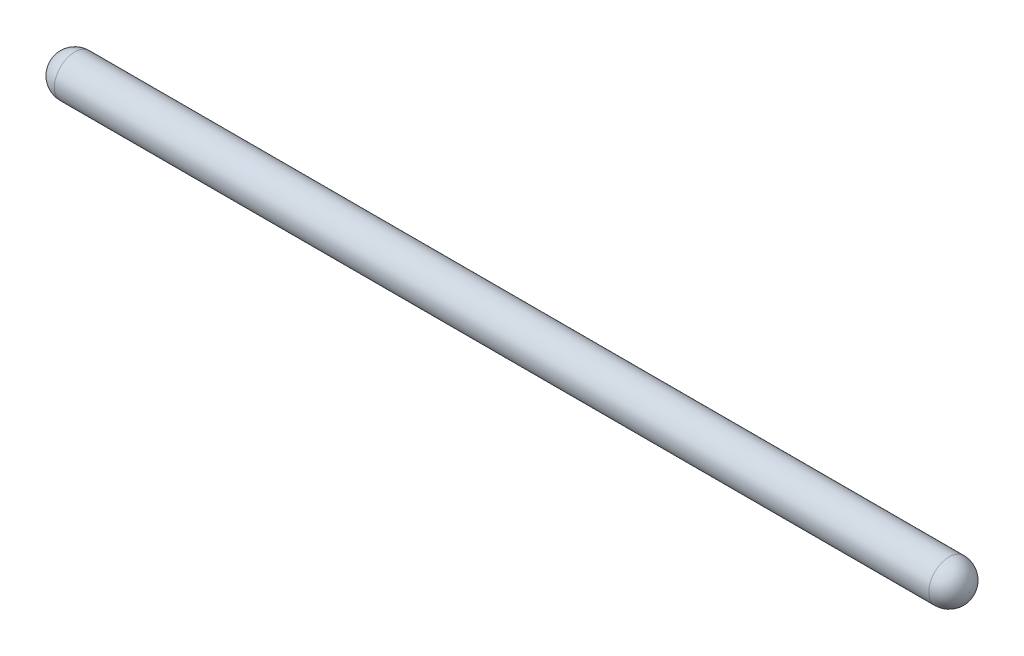
SolidWorks part; units mm, degrees
ref_plane "Front Plane" through (0, 0, 0) normal (0, 0, 1) x (1, 0, 0)
ref_plane "Top Plane" through (0, 0, 0) normal (0, 1, 0) x (1, 0, 0)
ref_plane "Right Plane" through (0, 0, 0) normal (1, 0, 0) x (0, 0, -1)
sketch "Sketch1" plane through (1051.9457, 0, 0) normal (1, 0, 0) x (0, 0, -1)
  circle A0 centre (-1240.6814, 1075.9802) radius 15.2222 construction
  circle A1 centre (-1240.6814, 1075.9802) radius 15.2222
extrude "Boss-Extrude1" add sketch "Sketch1" against normal blind 680
fillet "Fillet1" radius 15 2 edges at (1051.9457, 1075.9802, 1225.4592) (371.9457, 1075.9802, 1225.4592)
